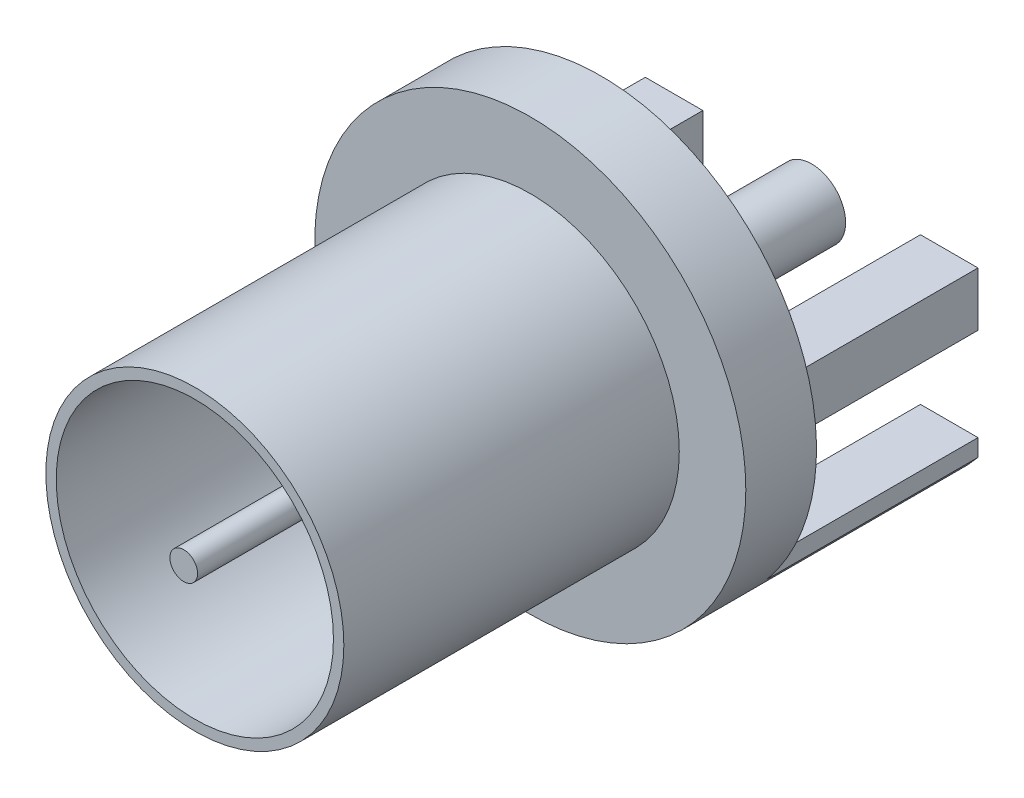
SolidWorks part; units mm, degrees
material "6061 Alloy"
ref_plane "Front Plane" through (0, 0, 0) normal (0, 0, 1) x (1, 0, 0)
ref_plane "Top Plane" through (0, 0, 0) normal (0, 1, 0) x (1, 0, 0)
ref_plane "Right Plane" through (0, 0, 0) normal (1, 0, 0) x (0, 0, -1)
sketch "Sketch1" plane through (0, 0, 0) normal (0, 0, 1) x (1, 0, 0)
  circle A0 centre (0, 0) radius 3.9497
  dimension "D1" = 7.8994
extrude "Boss-Extrude1" add sketch "Sketch1" along normal blind 1.2954
sketch "Sketch2" plane through (0, 0, 1.2954) normal (0, 0, 1) x (1, 0, 0)
  circle A0 centre (0, 0) radius 2.7305
  circle A1 centre (0, 0) radius 2.54
  dimension "D1" = 5.461
  dimension "D2" = 5.08
extrude "Boss-Extrude2" add sketch "Sketch2" along normal blind 6.1468
sketch "Sketch3" plane through (0, 0, 0) normal (0, 0, -1) x (-1, 0, 0)
  line L0 (1.9939, 0.4729) -> (3.048, 0.4729)
  line L1 (-3.048, 0.4953) -> (-1.9939, 0.4953)
  line L2 (-3.048, 0.4953) -> (-3.048, -0.4953)
  line L3 (-3.048, -0.4953) -> (-1.9939, -0.4953)
  line L4 (-1.9939, 0.4953) -> (-1.9939, -0.4953)
  line L5 (1.9939, 0.4729) -> (1.9939, -0.4953)
  line L6 (1.9939, -0.4953) -> (3.048, -0.4953)
  line L7 (3.048, 0.4729) -> (3.048, -0.4953)
  line L8 (-1.9939, -3.4095) -> (-1.9939, -2.1971)
  line L9 (-1.9939, -2.1971) -> (-3.048, -2.1971)
  line L10 (-3.048, -2.1971) -> (-3.048, -2.5119)
  line L11 (1.9939, -2.1971) -> (3.048, -2.1971)
  line L12 (3.048, -2.1971) -> (3.048, -2.5119)
  line L13 (1.9939, -2.1971) -> (1.9939, -3.4095)
  circle A0 centre (0, 0) radius 3.9497 construction
  arc A1 (-3.048, -2.5119) -> (-1.9939, -3.4095) centre (0, 0) ccw
  arc A2 (1.9939, -3.4095) -> (3.048, -2.5119) centre (0, 0) ccw
  dimension "D1" = 0.9906
  dimension "D2" = 1.0541
  dimension "D3" = 1.9939
  dimension "D4" = 0.4953
  dimension "D5" = 1.9939
  dimension "D6" = 0.4953
  dimension "D7" = 1.7018
extrude "Boss-Extrude3" add sketch "Sketch3" along normal blind 3.8608
sketch "Sketch4" plane through (0, 0, 0) normal (0, 0, -1) x (-1, 0, 0)
  circle A0 centre (0, 0) radius 0.6223
  dimension "D1" = 1.2446
extrude "Boss-Extrude4" add sketch "Sketch4" along normal blind 3.8608
sketch "Sketch5" plane through (0, 0, 1.2954) normal (0, 0, 1) x (1, 0, 0)
  circle A0 centre (0, 0) radius 0.254
extrude "Boss-Extrude5" add sketch "Sketch5" along normal blind 6.35
sketch "Sketch7" plane through (0, 0, 0) normal (0, 0, 1) x (1, 0, 0)
  circle A0 centre (0, 0) radius 2.947
  dimension "D1" = 5.8941
